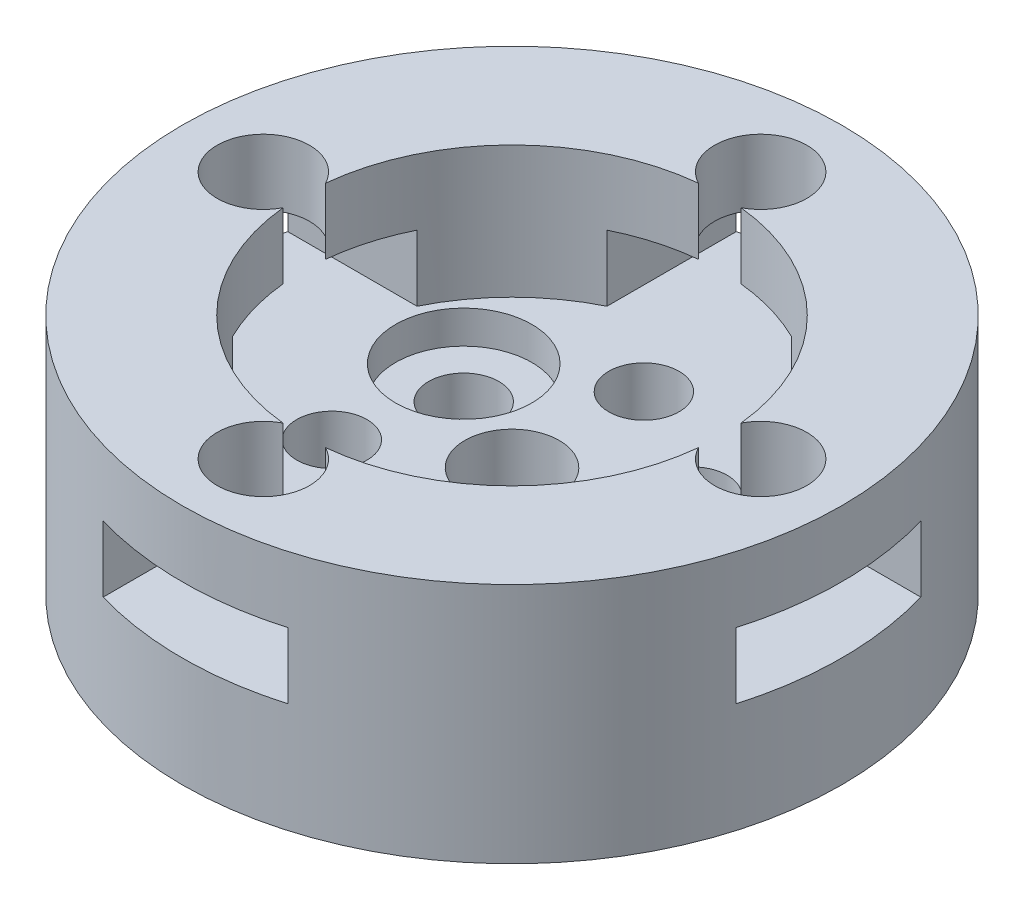
SolidWorks part; units mm, degrees
ref_plane "前视基准面" through (0, 0, 0) normal (0, 0, 1) x (1, 0, 0)
ref_plane "上视基准面" through (0, 0, 0) normal (0, 1, 0) x (1, 0, 0)
ref_plane "右视基准面" through (0, 0, 0) normal (1, 0, 0) x (0, 0, -1)
sketch "Sketch1" plane through (0, 0, 0) normal (0, 1, 0) x (1, 0, 0)
  line L0 (0, 11.2998) -> (0, -11.3131) construction
  circle A0 centre (0, 0) radius 10
  circle A1 centre (0, 0) radius 6 construction
  circle A2 centre (0, 6) radius 1.6
  circle A3 centre (5.1962, 3) radius 1.6
  circle A4 centre (5.1962, -3) radius 1.6
  circle A5 centre (0, -6) radius 1.6
  circle A6 centre (-5.1962, -3) radius 1.6
  circle A7 centre (-5.1962, 3) radius 1.6
  circle A8 centre (0, 0) radius 2.15
  dimension "D1" = 20
  dimension "D2" = 12
  dimension "D3" = 3.2
  dimension "D5" = 4.3
  dimension "D4" = 6
extrude "Boss-Extrude1" add sketch "Sketch1" along normal blind 5
sketch "Sketch2" plane through (0, 5, 0) normal (0, 1, 0) x (1, 0, 0)
  line L0 (0, 10.3978) -> (0, -10.7765) construction
  circle A0 centre (-5.1962, 3) radius 3.1
  circle A3 centre (5.1962, -3) radius 3.1
  circle A6 centre (0, 0) radius 6 construction
  circle A7 centre (0, 6) radius 3.1 [skipped]
  circle A8 centre (0, -6) radius 3.1 [skipped]
  circle A9 centre (-5.1962, -3) radius 3.1 [skipped]
  circle A10 centre (5.1962, 3) radius 3.1 [skipped]
  point P16 (0, 0)
  dimension "D1" = 6.2
  dimension "D2" = 6
extrude "Cut-Extrude2" cut sketch "Sketch2" against normal blind 1.5
sketch "Sketch3" plane through (0, 0, 0) normal (0, -1, 0) x (1, 0, 0)
  circle A0 centre (0, 0) radius 9.5
  circle A1 centre (0, 0) radius 15
  dimension "D1" = 30
  dimension "D2" = 19
extrude "Boss-Extrude2" add sketch "Sketch3" against normal blind 11
sketch "Sketch5" plane through (0, 11, 0) normal (0, 1, 0) x (1, 0, 0)
  line L0 (0, 16.1958) -> (0, -15.6011) construction
  line L1 (11.3137, 0) -> (0, 11.3137) construction
  line L2 (0, 11.3137) -> (-11.3137, 0) construction
  line L3 (-11.3137, 0) -> (0, -11.3137) construction
  line L4 (0, -11.3137) -> (11.3137, 0) construction
  circle A0 centre (0, 0) radius 8 construction
  circle A1 centre (0, 11.3137) radius 2.1
  circle A2 centre (11.3137, 0) radius 2.1
  circle A3 centre (0, -11.3137) radius 2.1
  circle A4 centre (-11.3137, 0) radius 2.1
  point P19 (0, 0)
  dimension "D1" = 16
  dimension "D2" = 4.2
  dimension "D3" = 4
extrude "Cut-Extrude3" cut sketch "Sketch5" against normal blind 3
sketch "Sketch7" plane through (0, 8, 0) normal (0, 1, 0) x (1, 0, 0)
  line L0 (0, 15.5155) -> (0, -16.6788) construction
  line L1 (-19.046, 0) -> (22.9688, 0) construction
  line L2 (-17.3137, 4.2) -> (-7.3137, 4.2)
  line L3 (-7.3137, 4.2) -> (-7.3137, -4.2)
  line L4 (-17.3137, 4.2) -> (-17.3137, -4.2)
  line L5 (-17.3137, -4.2) -> (-7.3137, -4.2)
  line L6 (4.2, 7.3137) -> (-4.2, 7.3137)
  line L7 (-4.2, 17.3137) -> (-4.2, 7.3137)
  line L8 (4.2, 17.3137) -> (-4.2, 17.3137)
  line L9 (4.2, 17.3137) -> (4.2, 7.3137)
  line L10 (7.3137, -4.2) -> (7.3137, 4.2)
  line L11 (17.3137, 4.2) -> (7.3137, 4.2)
  line L12 (17.3137, -4.2) -> (17.3137, 4.2)
  line L13 (17.3137, -4.2) -> (7.3137, -4.2)
  line L14 (-4.2, -7.3137) -> (4.2, -7.3137)
  line L15 (4.2, -17.3137) -> (4.2, -7.3137)
  line L16 (-4.2, -17.3137) -> (4.2, -17.3137)
  line L17 (-4.2, -17.3137) -> (-4.2, -7.3137)
  circle A0 centre (-11.3137, 0) radius 0.5 construction
  point P10 (-7.3137, 0)
  point P11 (-17.3137, 0)
  point P26 (0, 0)
  dimension "D5" = 1
  dimension "D1" = 4
  dimension "D2" = 4.2
  dimension "D3" = 10
  dimension "D4" = 4
extrude "Cut-Extrude4" cut sketch "Sketch7" against normal blind 3
